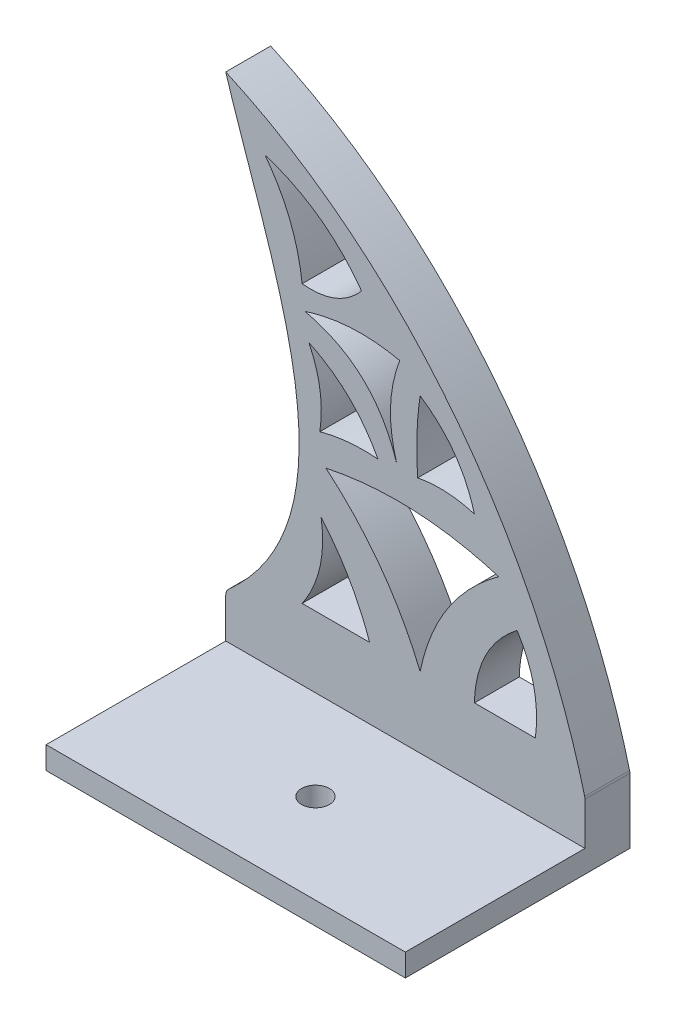
SolidWorks part; units mm, degrees
material "1060 Alloy"
ref_plane "Front Plane" through (0, 0, 0) normal (0, 0, 1) x (1, 0, 0)
ref_plane "Top Plane" through (0, 0, 0) normal (0, 1, 0) x (1, 0, 0)
ref_plane "Right Plane" through (0, 0, 0) normal (1, 0, 0) x (0, 0, -1)
sketch "Sketch1" plane through (0, 0, 0) normal (0, 0, 1) x (1, 0, 0)
  line L1 (0, 0) -> (101.6, 0)
  line L2 (0, 0) -> (0, 152.4)
  line L3 (0, 152.4) -> (101.6, 152.4)
  line L4 (101.6, 0) -> (101.6, 152.4)
  dimension "D1" = 101.6
  dimension "D2" = 152.4
extrude "Boss-Extrude1" add sketch "Sketch1" along normal blind 12.7 contours L2 L1 L4 L3
sketch "Sketch2" plane through (0, 0, 0) normal (0, 0, 1) x (1, 0, 0)
  line L0 (0, 152.4) -> (0, 279.4) construction
  line L1 (0, 152.4) -> (101.6, 152.4)
  line L3 (40.6766, 160.02) -> (21.6029, 160.02)
  line L4 (70.3278, 160.02) -> (87.5465, 160.02)
  spline S0 degree 3 poles (0, 279.4) (51.2861, 256.55) (87.8369, 205.9579) (101.6, 152.4) knots 0 0 0 0 1 1 1 1
  spline S1 degree 3 poles (0, 152.4) (39.7901, 186.8391) (12.3098, 238.8455) (0, 279.4) knots 0 0 0 0 1 1 1 1
  spline S2 degree 2 poles (26.9805, 183.8137) (28.9588, 170.8375) (21.6029, 160.02) knots 0 0 0 1 1 1
  spline S3 degree 2 poles (82.3961, 183.8137) (89.3396, 172.7738) (87.5465, 160.02) knots 0 0 0 1 1 1
  spline S4 degree 2 poles (23.5161, 224.8619) (28.2353, 215.2193) (26.6057, 204.5822) knots 0 0 0 1 1 1
  spline S5 degree 2 poles (54.9771, 227.5573) (66.6459, 219.8522) (70.3283, 206.2775) knots 0 0 0 1 1 1
  spline S6 degree 2 poles (21.6029, 238.3231) (31.8648, 237.2845) (38.4123, 244.9499) knots 0 0 0 1 1 1
  spline S7 degree 2 poles (26.9805, 183.8137) (36.1385, 173.1751) (40.6766, 160.02) knots 0 0 0 1 1 1
  spline S8 degree 2 poles (82.3961, 183.8137) (70.6714, 174.6636) (70.3278, 160.02) knots 0 0 0 1 1 1
  spline S9 degree 2 poles (54.9771, 160.02) (46.0835, 181.5476) (28.3421, 196.5298) knots 0 0 0 1 1 1
  spline S10 degree 2 poles (54.9771, 160.02) (59.3747, 181.4006) (77.1872, 194.3635) knots 0 0 0 1 1 1
  spline S11 degree 2 poles (28.3421, 196.5298) (53.0178, 201.7323) (77.1872, 194.3635) knots 0 0 0 1 1 1
  spline S12 degree 2 poles (26.6057, 204.5822) (34.7004, 206.7929) (43.0535, 206.088) knots 0 0 0 1 1 1
  spline S13 degree 2 poles (43.0535, 206.088) (36.2398, 218.9127) (23.5161, 224.8619) knots 0 0 0 1 1 1
  spline S14 degree 2 poles (70.3283, 206.2775) (62.3616, 208.669) (54.2871, 207.1099) knots 0 0 0 1 1 1
  spline S15 degree 2 poles (54.2871, 207.1099) (53.4821, 217.3917) (54.9771, 227.5573) knots 0 0 0 1 1 1
  spline S16 degree 2 poles (48.4004, 207.5354) (42.0542, 227.5662) (22.3756, 231.9373) knots 0 0 0 1 1 1
  spline S17 degree 2 poles (48.4004, 207.5354) (44.3936, 220.7345) (49.2258, 233.3158) knots 0 0 0 1 1 1
  spline S18 degree 2 poles (49.2258, 233.3158) (35.6412, 236.2679) (22.3756, 231.9373) knots 0 0 0 1 1 1
  spline S19 degree 2 poles (21.6029, 238.3231) (19.952, 252.9745) (11.0947, 264.6015) knots 0 0 0 1 1 1
  spline S20 degree 2 poles (11.0947, 264.6015) (28.0538, 259.2958) (38.4123, 244.9499) knots 0 0 0 1 1 1
  dimension "D1" = 127
extrude "Boss-Extrude3" add sketch "Sketch2" along normal blind 12.7 contours S1 L1 S0 S18 S17 S16 S13 S12 S4 S8 S3 L4 S2 S7 L3 S9 S11 S10 S14 S15 S5 S19 S20 S6
fillet "Fillet1" radius 2.54 2 edges at (101.6, 152.4, 6.35) (0, 152.4, 6.35)
fillet "Fillet2" radius 5.08 2 edges at (101.6, 0, 6.35) (0, 0, 6.35)
sketch "Sketch5" plane through (0, 0, 12.7) normal (0, 0, 1) x (1, 0, 0)
  line L1 (101.519, 133.6639) -> (101.6, 133.6639)
  line L2 (101.6, 5.08) -> (101.6, 152.0778) construction
  line L4 (101.6, 133.6639) -> (0, 133.6639)
  line L5 (101.6, 133.6639) -> (101.6, 0)
  line L6 (101.6, 0) -> (0, 0)
  line L7 (0, 133.6639) -> (0, 0)
  line M2 (5.08, 0) -> (96.52, 0)
  arc M3 (96.52, 0) -> (101.6, 5.08) centre (96.52, 5.08) ccw
  line M4 (101.6, 5.08) -> (101.6, 152.0778)
  line M9 (0, 151.2513) -> (0, 5.08)
  arc M10 (0, 5.08) -> (5.08, 0) centre (5.08, 5.08) ccw
extrude "Cut-Extrude2" cut sketch "Sketch5" against normal through all contours L1 L4 M9 M10 M2 M3 M4
sketch "Sketch8" plane through (0, 0, 12.7) normal (0, 0, 1) x (1, 0, 0)
  line L0 (0, 133.6639) -> (0, 151.2513) construction
  line L1 (101.6, 133.6639) -> (0, 133.6639)
  line L2 (101.6, 133.6639) -> (101.6, 140.0139)
  line L3 (101.6, 140.0139) -> (0, 140.0139)
  line L4 (0, 133.6639) -> (0, 140.0139)
  dimension "D1" = 6.35
extrude "Boss-Extrude4" add sketch "Sketch8" along normal blind 50.8
sketch "Sketch9" plane through (0, 140.0139, 0) normal (0, 1, 0) x (1, 0, 0)
  line L0 (50.7595, -12.7) -> (50.8, -63.5) construction
  line L1 (0, -12.7) -> (101.519, -12.7) construction
  line L2 (101.6, -63.5) -> (0, -63.5) construction
  circle A1 centre (50.7798, -38.1) radius 3.937
  dimension "D1" = 7.874
extrude "Cut-Extrude3" cut sketch "Sketch9" against normal through all
